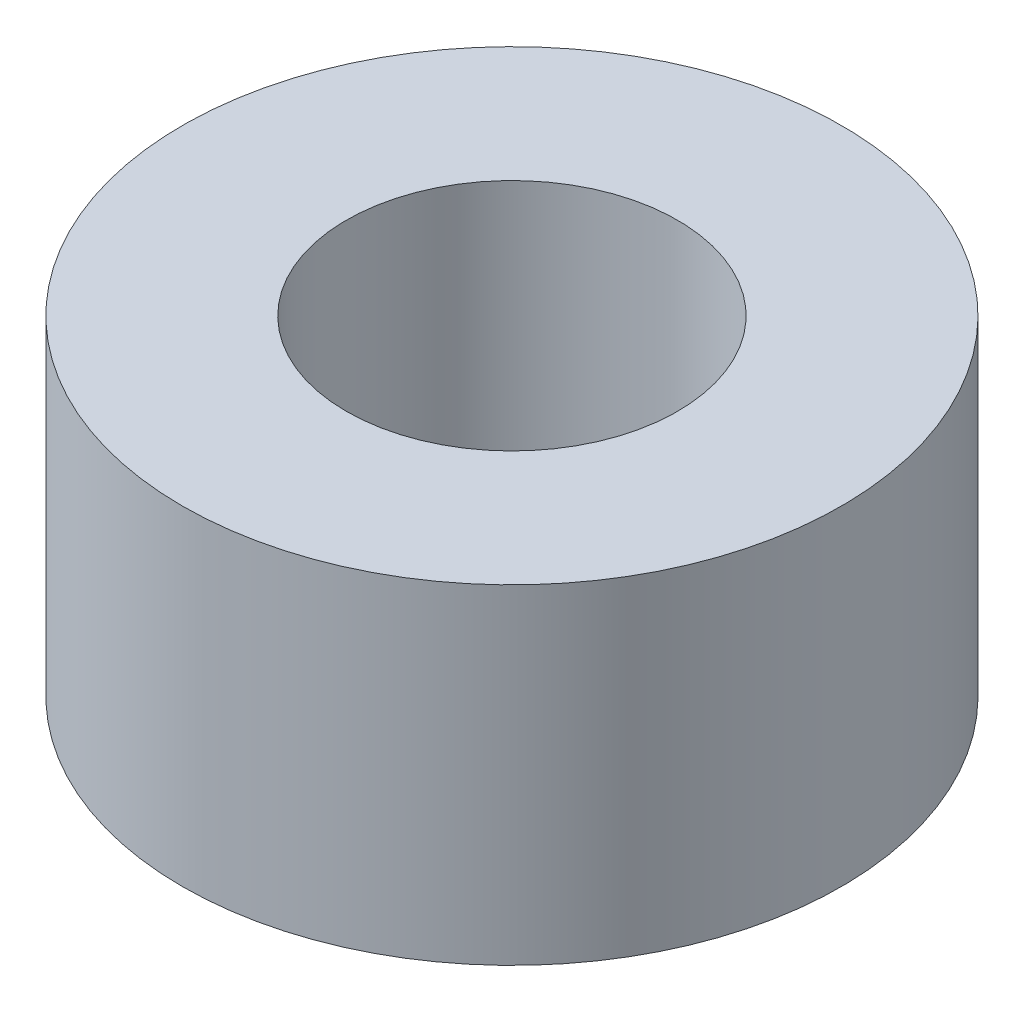
SolidWorks part; units mm, degrees
ref_plane "Front Plane" through (0, 0, 0) normal (0, 0, 1) x (1, 0, 0)
ref_plane "Top Plane" through (0, 0, 0) normal (0, 1, 0) x (1, 0, 0)
ref_plane "Right Plane" through (0, 0, 0) normal (1, 0, 0) x (0, 0, -1)
sketch "Sketch1" plane through (0, 0, 0) normal (0, 1, 0) x (1, 0, 0)
  circle A0 centre (0, 0) radius 10
  dimension "D1" = 20
extrude "Boss-Extrude1" add sketch "Sketch1" along normal blind 10
sketch "Sketch2" plane through (0, 0, 0) normal (0, 1, 0) x (1, 0, 0)
  circle A0 centre (0, 0) radius 5.025
  dimension "D1" = 10.05
extrude "Cut-Extrude1" cut sketch "Sketch2" along normal blind 10
